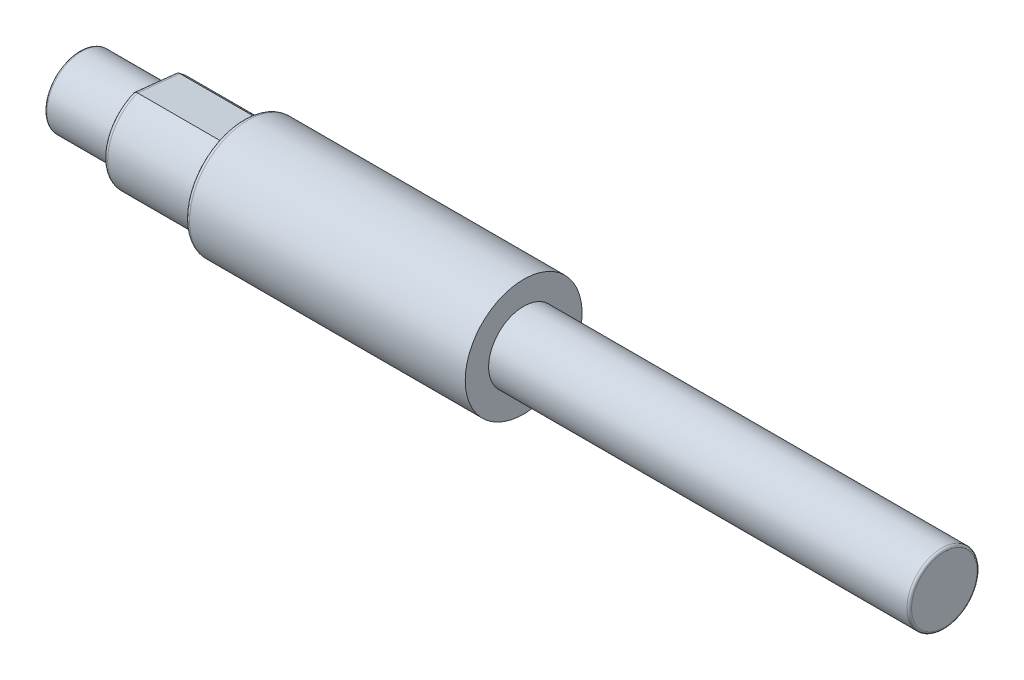
SolidWorks part; units mm, degrees
ref_plane "前视基准面" through (0, 0, 0) normal (0, 0, 1) x (1, 0, 0)
ref_plane "上视基准面" through (0, 0, 0) normal (0, 1, 0) x (1, 0, 0)
ref_plane "右视基准面" through (0, 0, 0) normal (1, 0, 0) x (0, 0, -1)
sketch "草图1" plane through (0, 0, 0) normal (1, 0, 0) x (0, 0, -1)
  circle A0 centre (0, 0) radius 1.5
extrude "凸台-拉伸1" add sketch "草图1" along normal blind 37
sketch "草图2" plane through (0, 0, 0) normal (-1, 0, 0) x (0, 0, 1)
  circle A0 centre (0, 0) radius 2.5
  circle A1 centre (0, 0) radius 1
sketch "草图3" plane through (0, 0, 0) normal (1, 0, 0) x (0, 0, -1)
  line L0 (1.0937, 1.6744) -> (-0.72, 1.8659)
  arc A0 (-0.72, 1.8659) -> (1.0937, 1.6744) centre (0, 0) ccw
  circle A1 centre (0, 0) radius 1
  dimension "D1" = 1.78
extrude "凸台-拉伸2" add sketch "草图2" against normal blind 12 from offset 7 offset against normal yes
extrude "凸台-拉伸4" add sketch "草图3" along normal blind 4 from offset 3
fillet "圆角1" radius 0.1 2 edges at (37, 0, -1.5) (0, 0, -1.5)
fillet "圆角2" radius 0.2 3 edges at (7, 0, 2.5) (3, 1.7702, -0.1868) (3, -1.989, 0.2099)
